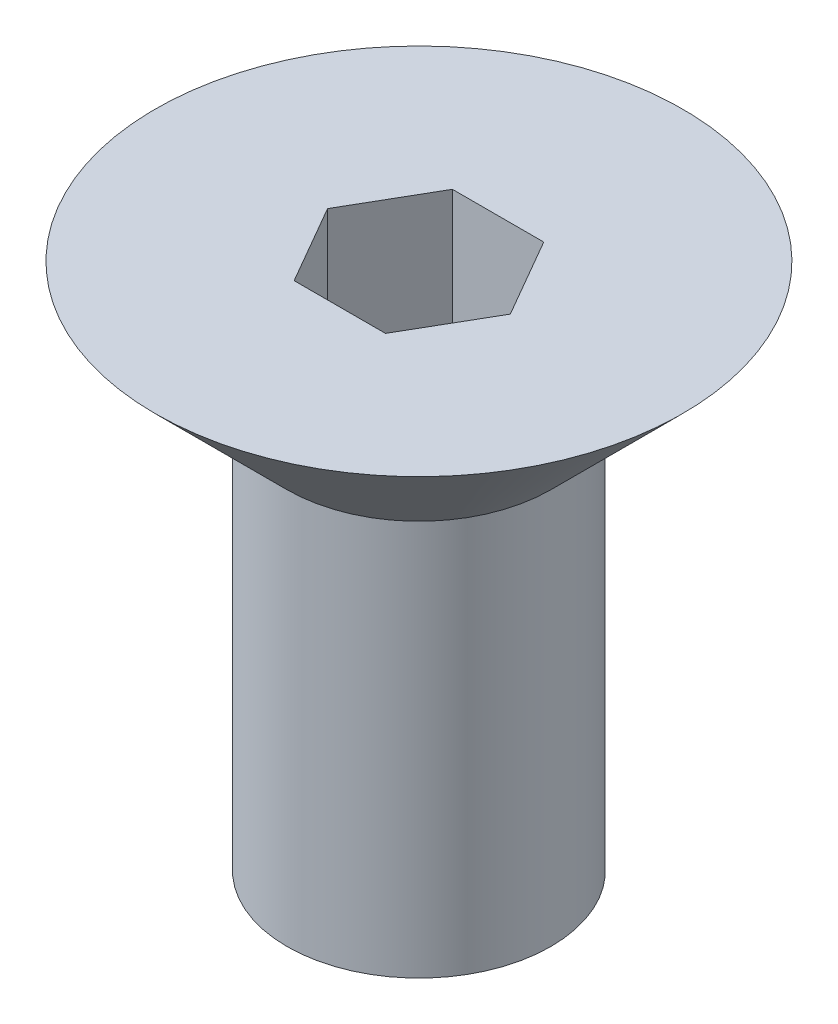
SolidWorks part; units mm, degrees
material "AISI 304"
ref_plane "Front Plane" through (0, 0, 0) normal (0, 0, 1) x (1, 0, 0)
ref_plane "Top Plane" through (0, 0, 0) normal (0, 1, 0) x (1, 0, 0)
ref_plane "Right Plane" through (0, 0, 0) normal (1, 0, 0) x (0, 0, -1)
sketch "Sketch1" plane through (0, 0, 0) normal (0, 0, 1) x (1, 0, 0)
  line L0 (0, 61.6916) -> (0, -59.3578) construction
  line L1 (0, -10) -> (2.5, -10)
  line L2 (2.5, -10) -> (2.5, -2.5)
  line L3 (-4.1135, -0.8865) -> (-2.5, -2.5) construction
  line L5 (5, 0) -> (0, 0)
  line L6 (0, 0) -> (0, -10)
  line L7 (2.5, -2.5) -> (5, 0)
  dimension "D1" = 90
  dimension "D2" = 10
  dimension "D3" = 5
  dimension "D5" = 10
revolve "Revolve1" add sketch "Sketch1" angle 360 about L0
sketch "Sketch2" plane through (0, 0, 0) normal (0, 1, 0) x (-1, 0, 0)
  line L1 (-0.866, -1.5) -> (0.866, -1.5)
  line L2 (0.866, -1.5) -> (1.7321, 0)
  line L3 (1.7321, 0) -> (0.866, 1.5)
  line L4 (0.866, 1.5) -> (-0.866, 1.5)
  line L5 (-0.866, 1.5) -> (-1.7321, 0)
  line L6 (-1.7321, 0) -> (-0.866, -1.5)
  circle A0 centre (0, 0) radius 1.5 construction
  dimension "D1" = 3
extrude "Cut-Extrude1" cut sketch "Sketch2" against normal blind 2.5
